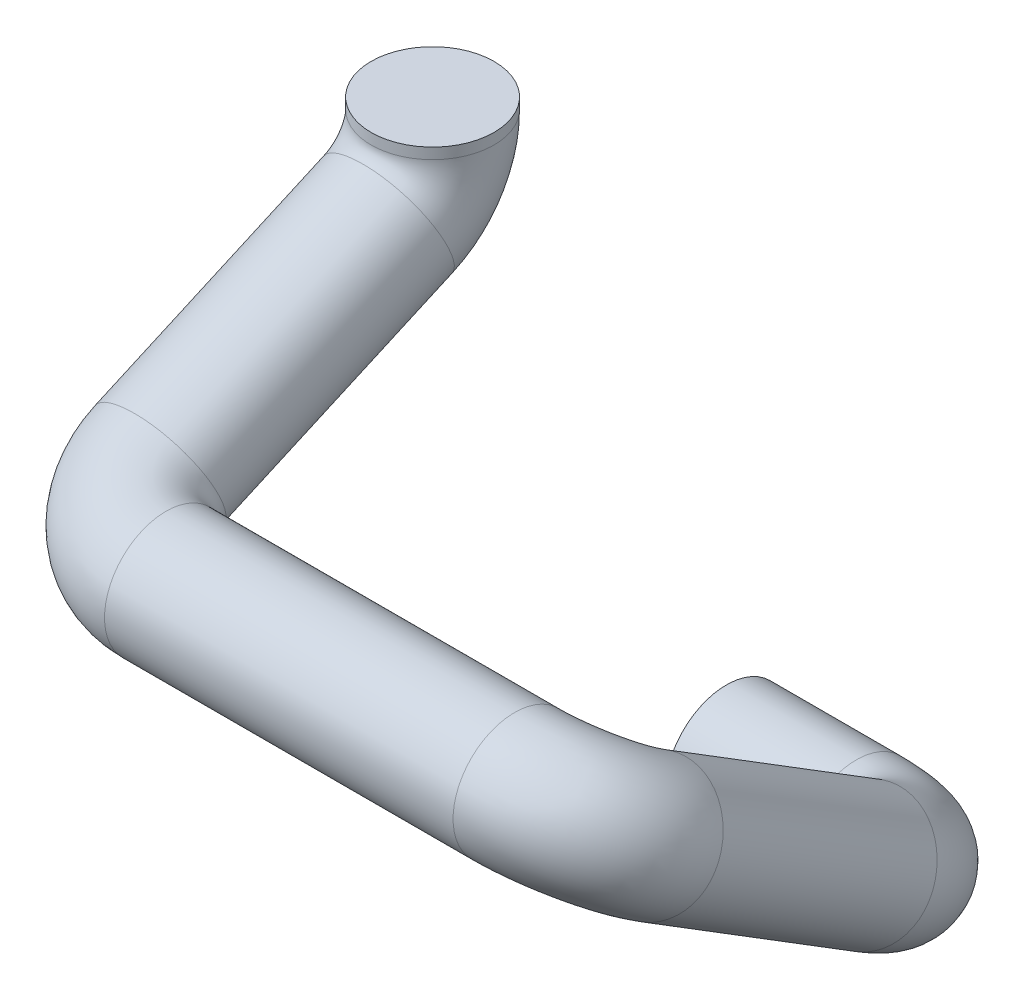
SolidWorks part; units mm, degrees
ref_plane "前视基准面" through (0, 0, 0) normal (0, 0, 1) x (1, 0, 0)
ref_plane "上视基准面" through (0, 0, 0) normal (0, 1, 0) x (1, 0, 0)
ref_plane "右视基准面" through (0, 0, 0) normal (1, 0, 0) x (0, 0, -1)
sketch "草图1" plane through (0, 0, 0) normal (0, 0, 1) x (1, 0, 0)
  line L0 (0, 62) -> (0, 0) construction
  line L1 (0, 0) -> (43, 0) construction
  dimension "D1" = 62
  dimension "D2" = 43
sketch "草图2" plane through (0, 0, 0) normal (1, 0, 0) x (0, 0, -1)
  line L0 (0, 62) -> (0, 60.4049)
  line L1 (0, 62) -> (0, 0) construction
  line L2 (0, 31) -> (-50, 31) construction
  line L3 (-6.5259, 50.3559) -> (-50, 31) construction
  line L4 (-6.5259, 50.3559) -> (-39.951, 35.4741)
  arc A0 (0, 60.4049) -> (-6.5259, 50.3559) centre (-11, 60.4049) cw
  point P11 (0, 53.2614)
  dimension "D3" = 11
  dimension "D1" = 24
  dimension "D2" = 50
  dimension "D4" = 11
ref_plane "基准面1" through (0, 31, 0) normal (0, 1, 0) x (1, 0, 0)
sketch "草图3" plane through (0, 31, 0) normal (0, 1, 0) x (1, 0, 0)
  line L0 (0, -50) -> (73, -50) construction
  line L1 (0, 0) -> (0, -50) construction
  line L3 (0, 0) -> (43, 0) construction
  point P4 (0, 0)
  point P5 (0, -40.2326)
  dimension "D1" = 73
  dimension "D2" = 50
ref_plane "基准面2" through (73, 0, 0) normal (1, 0, 0) x (0, 0, -1)
sketch "草图5" plane through (73, 0, 0) normal (1, 0, 0) x (0, 0, -1)
  line L0 (-50, 31) -> (0, 0)
sketch "草图6" plane through (0, 0, 0) normal (0, 0, 1) x (1, 0, 0)
  line L0 (73, 0) -> (43, 0)
  line L1 (73, 31) -> (73, 0) construction
ref_plane "基准面3" through (0, 62, 0) normal (0, 1, 0) x (1, 0, 0)
sketch "草图8" plane through (0, 62, 0) normal (0, 1, 0) x (1, 0, 0)
  circle A1 centre (0, 0) radius 9
  point P0 (0, 0)
  dimension "D1" = 18
sketch3d "3D草图5"
  line L0 (0, 62, 0) -> (0, 60.4049, 0)
  line L1 (0, 50.3559, 6.5259) -> (0, 35.4741, 39.951)
  line L2 (11, 31, 50) -> (62, 31, 50)
  line L3 (73, 25.2037, 40.6511) -> (73, 5.7963, 9.3489)
  line L4 (62, 0, 0) -> (43, 0, 0)
  arc A0 (73, 5.7963, 9.3489) -> (62, 0, 0) centre (62, 5.7963, 9.3489) ccw
  arc A1 (62, 31, 50) -> (73, 25.2037, 40.6511) centre (62, 25.2037, 40.6511) ccw
  arc A2 (0, 35.4741, 39.951) -> (11, 31, 50) centre (11, 35.4741, 39.951) ccw
  arc A3 (0, 60.4049, 0) -> (0, 50.3559, 6.5259) centre (0, 60.4049, 11) ccw
  point P14 (73, 0, 0)
  point P15 (62, 15.1453, 3.5526)
  point P18 (73, 31, 50)
  point P19 (62, 34.5526, 34.8547)
  point P22 (0, 31, 50)
  point P23 (11, 45.5231, 44.4251)
  point P26 (0, 53.2614, 0)
  point P27 (-11, 60.4049, 11)
  dimension "D1" = 11
  dimension "D2" = 11
sweep "扫描5" add profiles "草图8" path "3D草图5"
